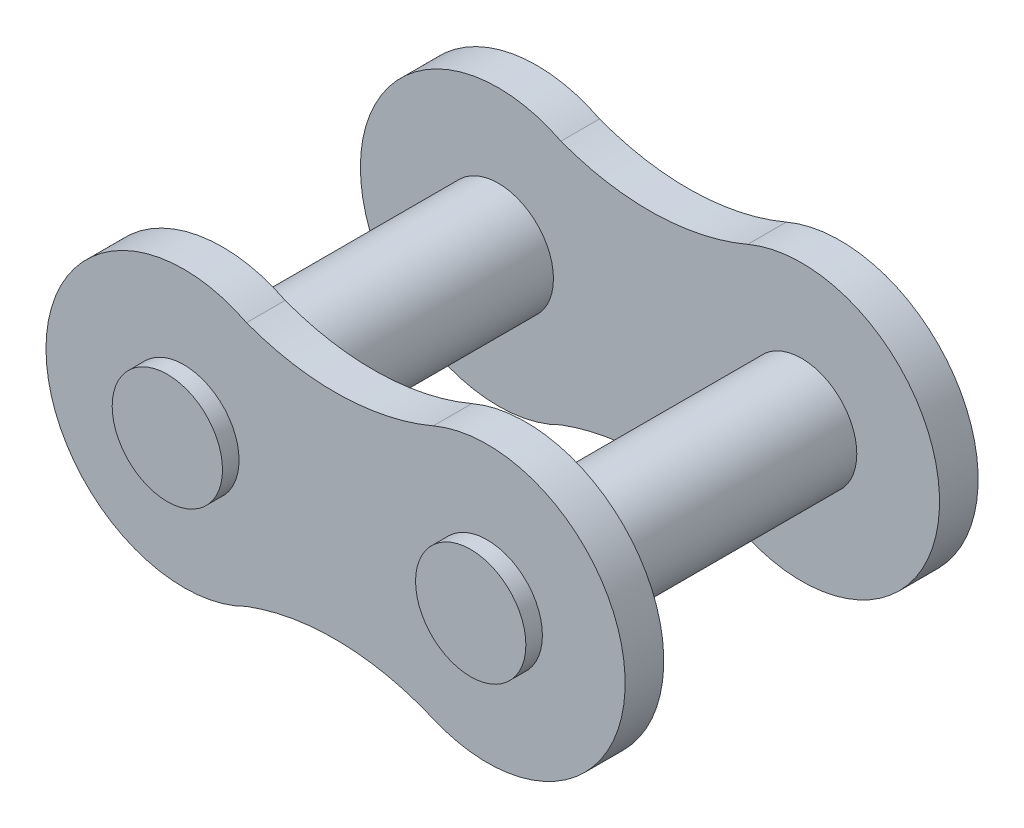
SolidWorks part; units mm, degrees
ref_plane "Front Plane" through (0, 0, 0) normal (0, 0, 1) x (1, 0, 0)
ref_plane "Top Plane" through (0, 0, 0) normal (0, 1, 0) x (1, 0, 0)
ref_plane "Right Plane" through (0, 0, 0) normal (1, 0, 0) x (0, 0, -1)
sketch "Sketch1" plane through (0, 0, 0) normal (0, 0, 1) x (1, 0, 0)
  line L0 (-62.0872, 0) -> (94.3096, 0) construction
  arc A0 (-1.6144, 2.2272) -> (-1.6144, -2.2272) centre (-2.75, 0) ccw
  arc A1 (1.7724, -2.3009) -> (1.7724, 2.3009) centre (2.75, 0) ccw
  arc A2 (-1.6144, 2.2272) -> (1.7724, 2.3009) centre (-0.0133, 6.504) ccw
  arc A3 (-1.6144, -2.2272) -> (1.7724, -2.3009) centre (-0.0133, -6.504) cw
  circle A4 centre (-2.75, 0) radius 1
  circle A5 centre (2.75, 0) radius 1
  dimension "D3" = 5
  dimension "D4" = 5
  dimension "D5" = 2
  dimension "D6" = 2
  dimension "D7" = 4.5667
  dimension "D1" = 5.5
  dimension "D2" = 2.75
extrude "Boss-Extrude1" add sketch "Sketch1" along normal blind 0.7
ref_plane "Plane1" through (0, 0, -2.5) normal (0, 0, -1) x (-1, 0, 0)
mirror "Mirror1" about plane through (0, 0, -2.5) normal (0, 0, -1) of bodies 101
sketch "Sketch2" plane through (0, 0, -2.5) normal (0, 0, -1) x (-1, 0, 0)
  circle A0 centre (-2.75, 0) radius 1
  circle A1 centre (2.75, 0) radius 1
extrude "Boss-Extrude2" add sketch "Sketch2" along normal mid plane 7
